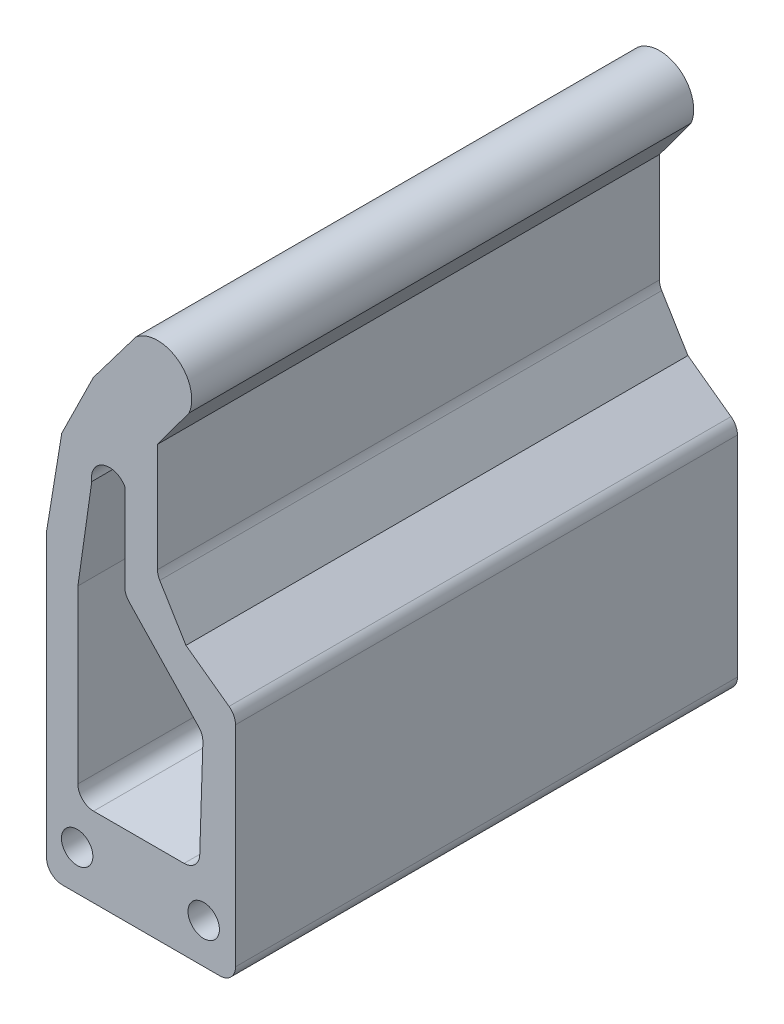
SolidWorks part; units mm, degrees
ref_plane "Front Plane" through (0, 0, 0) normal (0, 0, 1) x (1, 0, 0)
ref_plane "Top Plane" through (0, 0, 0) normal (0, 1, 0) x (1, 0, 0)
ref_plane "Right Plane" through (0, 0, 0) normal (1, 0, 0) x (0, 0, -1)
other "Graphic1"
ref_plane "Plane1" through (0, 0, 40) normal (0, 0, 1) x (1, 0, 0)
sketch "Sketch1" plane through (0, 0, 40) normal (0, 0, 1) x (1, 0, 0)
  line L0 (-300, 367) -> (-300, 348)
  line L1 (-300, 348) -> (-287.9516, 348)
  line L2 (-287.9516, 348) -> (-287.9516, 362.8718)
  line L3 (-287.9516, 362.8718) -> (-291.1109, 365.1664)
  line L4 (-291.1109, 365.1664) -> (-292.9258, 368.1591)
  line L5 (-292.9258, 368.1591) -> (-292.9258, 375.3591)
  line L6 (-292.9258, 375.3591) -> (-290.9105, 378.0975)
  line L7 (-300, 367) -> (-299.0296, 372.921)
  line L8 (-299.0296, 372.921) -> (-297.0124, 377.0093)
  line L9 (-297.0124, 377.0093) -> (-294.3, 380.6)
  arc A0 (-294.3, 380.6) -> (-290.9105, 378.0975) centre (-292.9147, 378.9296) cw
  point P15 (-287.9516, 362.8718)
extrude "Boss-Extrude1" add sketch "Sketch1" along normal blind 32
sketch "Sketch2" plane through (0, 0, 72) normal (0, 0, 1) x (1, 0, 0)
  line L0 (-297.1166, 371.2077) -> (-298, 365)
  line L1 (-298, 365) -> (-298, 353.0704)
  line L2 (-298, 353.0704) -> (-290.2634, 353.0704)
  line L3 (-290.2634, 353.0704) -> (-290.0188, 360.779)
  line L4 (-290.0188, 360.779) -> (-295.01, 366.0466)
  line L5 (-295.01, 366.0466) -> (-295.01, 371.9952)
  arc A0 (-297.1166, 371.2077) -> (-295.01, 371.9952) centre (-295.9914, 371.409) cw
  point P11 (-295.01, 371.9952)
extrude "Cut-Extrude1" cut sketch "Sketch2" against normal blind 32
sketch "Sketch3" plane through (0, 0, 72) normal (0, 0, 1) x (1, 0, 0)
  circle A0 centre (-298.0464, 350.5461) radius 1
  circle A1 centre (-289.9795, 350.5461) radius 1
extrude "Cut-Extrude2" cut sketch "Sketch3" against normal blind 32
fillet "Fillet2" radius 1 8 edges at (-292.9258, 368.1591, 56) (-287.9516, 362.8718, 56) (-287.9516, 348, 56) (-300, 348, 56) (-290.0188, 360.779, 56) (-295.01, 366.0466, 56) (-290.2634, 353.0704, 56) (-298, 353.0704, 56)
